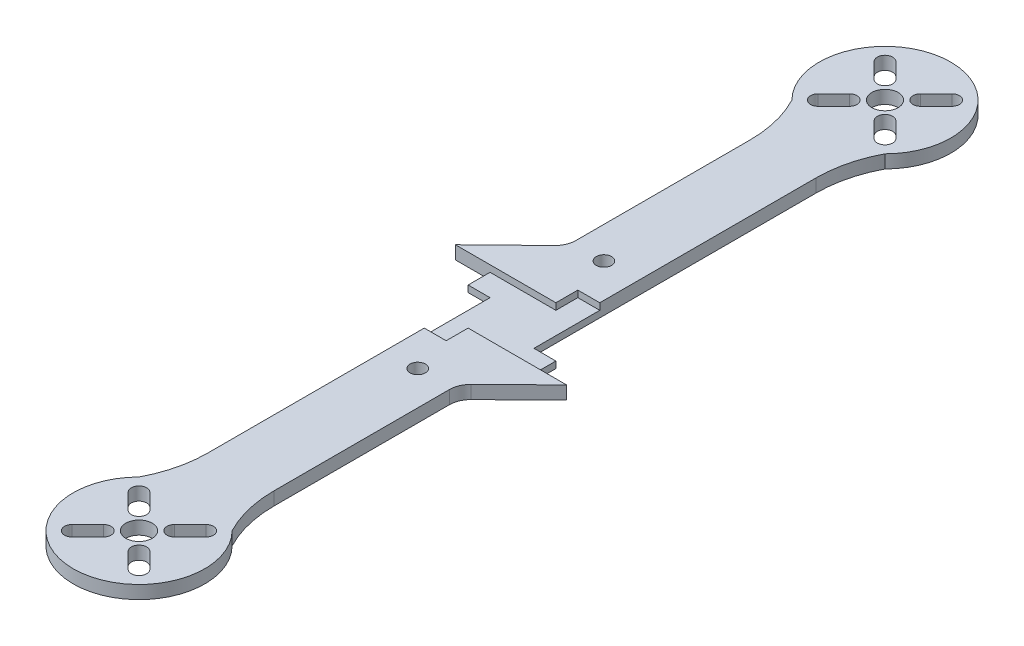
SolidWorks part; units mm, degrees
material "ABS"
ref_plane "Front Plane" through (0, 0, 0) normal (0, 0, 1) x (1, 0, 0)
ref_plane "Top Plane" through (0, 0, 0) normal (0, 1, 0) x (1, 0, 0)
ref_plane "Right Plane" through (0, 0, 0) normal (1, 0, 0) x (0, 0, -1)
sketch "Sketch1" plane through (0, 0, 0) normal (0, 1, 0) x (1, 0, 0)
  line L0 (-19.3064, 0) -> (26.0375, 0) construction
  line L3 (-7.451, -61.7809) -> (-7.451, 61.7809)
  line L4 (7.549, -61.7809) -> (7.549, 61.7809)
  arc A6 (10.6556, 74.3934) -> (-10.5576, 74.3934) centre (0.049, 85) ccw
  arc A12 (-7.451, 61.7809) -> (-10.5576, 74.3934) centre (-34.607, 61.7809) ccw
  arc A13 (7.549, 61.7809) -> (10.6556, 74.3934) centre (34.705, 61.7809) cw
  circle A14 centre (0.049, 85) radius 3
  circle A23 centre (-6.6685, 91.7175) radius 1.75
  circle A24 centre (-5.6079, 79.3431) radius 1.75
  circle A25 centre (5.7059, 90.6569) radius 1.75
  circle A26 centre (6.7665, 78.2825) radius 1.75
  circle A27 centre (0, 20) radius 1.5
  circle A28 centre (5.7059, -90.6569) radius 1.75
  circle A29 centre (-6.6685, -91.7175) radius 1.75
  circle A30 centre (0.049, -85) radius 3
  circle A31 centre (6.7665, -78.2825) radius 1.75
  circle A32 centre (-5.6079, -79.3431) radius 1.75
  arc A33 (7.549, -61.7809) -> (10.6556, -74.3934) centre (34.705, -61.7809) ccw
  arc A34 (10.6556, -74.3934) -> (-10.5576, -74.3934) centre (0.049, -85) cw
  arc A35 (-7.451, -61.7809) -> (-10.5576, -74.3934) centre (-34.607, -61.7809) cw
  circle A36 centre (0, -20) radius 1.5
  point P41 (7.549, 0)
  point P42 (-7.451, 0)
  dimension "D1" = 8
  dimension "D2" = 8
  dimension "D3" = 9.5
  dimension "D4" = 9.5
  dimension "D5" = 3.5
  dimension "D6" = 3.5
  dimension "D7" = 6
  dimension "D10" = 3.5
  dimension "D11" = 3.5
  dimension "D9" = 3
  dimension "D8" = 15
  dimension "D12" = 20
  dimension "D13" = 20
  dimension "D14" = 170
extrude "Boss-Extrude2" add sketch "Sketch1" along normal blind 3
sketch "Sketch3" plane through (0, 3, 0) normal (0, 1, 0) x (1, 0, 0)
  line L0 (-47.0006, 0) -> (46.456, 0) construction
  line L1 (7.549, -61.7809) -> (7.549, 61.7809) construction
  line L2 (-7.549, -7.5) -> (7.549, -7.5)
  line L3 (-7.549, -7.5) -> (-7.549, 7.5)
  line L4 (-7.549, 7.5) -> (7.549, 7.5)
  line L5 (7.549, -7.5) -> (7.549, 7.5)
  line L6 (-7.549, -7.5) -> (7.549, 7.5) construction
  line L7 (-7.549, 7.5) -> (7.549, -7.5) construction
  point P3 (0, 0)
  dimension "D1" = 15
extrude "Cut-Extrude1" cut sketch "Sketch3" against normal blind 1.5
sketch "Sketch4" plane through (0, 1.5, 0) normal (0, 1, 0) x (1, 0, 0)
  line L10 (-13.8473, 13.8237) -> (-7.4707, 7.5) construction
  line L11 (7.549, -7.5) -> (19.9805, -7.5)
  line L12 (7.549, -7.5) -> (7.549, -19.7239)
  line L13 (-7.2086, 7.5) -> (-20.3535, 7.5)
  line L14 (7.549, 7.5) -> (-7.451, 7.5) construction
  line L15 (-20.3535, 7.5) -> (-7.2086, 20.2761)
  line L16 (-7.2086, 20.2761) -> (-7.2086, 7.5)
  line L17 (19.9805, -7.5) -> (7.549, -19.7239)
  line L18 (7.6545, -7.5) -> (13.7913, -13.5859) construction
  point P1 (-0.1865, 0.2761)
  point P3 (0, 0)
extrude "Boss-Extrude5" add sketch "Sketch4" along normal mid plane 3
sketch "Sketch5" plane through (0, 3, 0) normal (0, 1, 0) x (1, 0, 0)
  line L18 (-2.451, -7.5) -> (-7.451, -7.5)
  line L21 (2.549, 7.5) -> (7.549, 7.5)
  line L23 (7.549, 7.5) -> (2.549, 7.5)
  line L24 (7.549, 7.5) -> (7.549, 12.5)
  line L25 (7.549, 12.5) -> (2.549, 12.5)
  line L26 (2.549, 7.5) -> (2.549, 12.5)
  line L27 (-7.451, -7.5) -> (-2.451, -7.5)
  line L28 (-7.451, -7.5) -> (-7.451, -12.5)
  line L29 (-7.451, -12.5) -> (-2.451, -12.5)
  line L30 (-2.451, -7.5) -> (-2.451, -12.5)
  line M10 (-20.3535, 7.5) -> (7.549, 7.5)
  line M11 (7.549, 7.5) -> (7.549, 61.7809)
  dimension "D1" = 5
  dimension "D2" = 5
  dimension "D3" = 5
  dimension "D4" = 5
extrude "Cut-Extrude2" cut sketch "Sketch5" against normal blind 1.5 contours L26 L25 M10 M11 | L30 L18 L28 L29
sketch "Sketch6" plane through (0, 3, 0) normal (0, 1, 0) x (1, 0, 0)
  line L0 (7.549, -19.7239) -> (8.9751, -18.3217)
  line L1 (7.549, -19.7239) -> (19.9805, -7.5) construction
  line L3 (7.549, -61.7809) -> (7.549, -19.7239) construction
  line L4 (7.549, -21.7239) -> (7.549, -19.7239)
  line L5 (-7.451, 20.0405) -> (-8.8852, 18.6465)
  line L6 (-7.451, 20.0405) -> (-20.3535, 7.5) construction
  line L8 (-7.451, 61.7809) -> (-7.451, 20.0405) construction
  line L9 (-7.451, 22.0405) -> (-7.451, 20.0405)
  arc A0 (8.9751, -18.3217) -> (7.549, -21.7239) centre (12.3205, -21.7239) ccw
  arc A1 (-8.8852, 18.6465) -> (-7.451, 22.0405) centre (-12.1839, 22.0405) ccw
  dimension "D1" = 2
  dimension "D2" = 2
  dimension "D3" = 2
  dimension "D4" = 2
extrude "Boss-Extrude7" add sketch "Sketch6" against normal blind 3
sketch "Sketch7" plane through (0, 1.5, 0) normal (0, 1, 0) x (1, 0, 0)
  line L0 (-7.451, -12.5) -> (-7.451, 7.5) construction
  line L1 (2.549, 7.5) -> (7.549, 7.5)
  line L2 (2.549, 7.5) -> (2.549, 12.5)
  line L3 (2.549, 12.5) -> (7.549, 12.5)
  line L4 (7.549, 7.5) -> (7.549, 12.5)
  line L5 (-2.451, -12.5) -> (-7.451, -12.5)
  line L6 (-2.451, -12.5) -> (-2.451, -7.5)
  line L7 (-2.451, -7.5) -> (-7.451, -7.5)
  line L8 (-7.451, -12.5) -> (-7.451, -7.5)
sketch "Sketch11" plane through (0, 1.5, 0) normal (0, 1, 0) x (1, 0, 0)
  line L1 (7.549, -7.5) -> (12.549, -7.5)
  line L2 (7.549, -7.5) -> (7.549, -2.5)
  line L3 (7.549, -2.5) -> (12.549, -2.5)
  line L4 (12.549, -7.5) -> (12.549, -2.5)
  line L5 (-7.451, 7.5) -> (-12.451, 7.5)
  line L6 (-7.451, 7.5) -> (-7.451, 2.5)
  line L7 (-7.451, 2.5) -> (-12.451, 2.5)
  line L8 (-12.451, 7.5) -> (-12.451, 2.5)
  dimension "D1" = 5
  dimension "D2" = 5
  dimension "D3" = 5
  dimension "D4" = 5
extrude "Boss-Extrude11" add sketch "Sketch11" against normal blind 1.5
sketch "Sketch13" plane through (0, 3, 0) normal (0, 1, 0) x (1, 0, 0)
  line L0 (40.0441, 0) -> (-47.62, 0) construction
  circle A0 centre (0, -20) radius 1.5
  circle A1 centre (0, 20) radius 1.5
extrude "Boss-Extrude13" add sketch "Sketch13" against normal blind 3
sketch "Sketch14" plane through (0, 3, 0) normal (0, 1, 0) x (1, 0, 0)
  line L0 (27.9035, 0) -> (-28.3453, 0) construction
  circle A0 centre (-0.2209, -21.2132) radius 1.5
  circle A1 centre (-0.2209, 21.2132) radius 1.5
  dimension "D3" = 3
  dimension "D4" = 3
  dimension "D1" = 42.4264
extrude "Cut-Extrude6" cut sketch "Sketch14" against normal through all
sketch "Sketch15" plane through (0, 3, 0) normal (0, 1, 0) x (1, 0, 0)
  circle A0 centre (-5.6079, 79.3431) radius 1.75
  circle A1 centre (6.7665, 78.2825) radius 1.75
  circle A2 centre (-6.6685, 91.7175) radius 1.75
  circle A3 centre (5.7059, 90.6569) radius 1.75
extrude "Boss-Extrude14" add sketch "Sketch15" against normal through all
sketch "Sketch16" plane through (0, 3, 0) normal (0, 1, 0) x (1, 0, 0)
  circle A2 centre (-6.6685, 78.2825) radius 1.75
  circle A3 centre (5.7059, 79.3431) radius 1.75
  circle A4 centre (6.7665, 91.7175) radius 1.75
  circle A5 centre (-5.6101, 90.6591) radius 1.75
  dimension "D5" = 3.5
  dimension "D6" = 3.5
  dimension "D7" = 3.5
  dimension "D8" = 3.5
extrude "Cut-Extrude7" cut sketch "Sketch16" against normal through all
sketch "Sketch17" plane through (0, 3, 0) normal (0, 1, 0) x (1, 0, 0)
  circle A0 centre (5.7059, 79.3431) radius 2.2546
  circle A1 centre (-6.6685, 78.2825) radius 2.9663
  circle A2 centre (-5.6101, 90.6591) radius 2.6365
  circle A3 centre (6.7665, 91.7175) radius 1.9965
  circle A4 centre (-6.6685, -91.7175) radius 2.525
  circle A5 centre (-5.6079, -79.3431) radius 3.3131
  circle A6 centre (6.7665, -78.2825) radius 2.2622
  circle A7 centre (5.7059, -90.6569) radius 2.3533
extrude "Boss-Extrude15" add sketch "Sketch17" against normal blind 3
sketch "Sketch18" plane through (0, 3, 0) normal (0, 1, 0) x (1, 0, 0)
  line L5 (0.049, -85) -> (-20.908, -85)
  line L6 (-20.908, -85) -> (24.5464, -85)
  line L11 (0.049, -105.9248) -> (0.049, -64.2488)
  line L12 (0.049, -85) -> (-2.7794, -87.8284)
  line L18 (-10.5576, -95.6066) -> (-8.7954, -93.8445)
  line L21 (0.049, -85) -> (-10.5576, -74.3934)
  line L22 (-10.5576, -74.3934) -> (0.049, -85)
  line L23 (0.049, -85) -> (10.6556, -95.6066)
  line L24 (52.5615, 0) -> (-59.544, 0) construction
  line L25 (0.049, -85) -> (-2.7794, -87.8284)
  line L30 (6.0476, -79.0014) -> (-2.7794, -87.8284) construction
  line L31 (8.8935, -91.3696) -> (5.3523, -87.8284)
  line L33 (0.049, -85) -> (-2.7794, -87.8284)
  line L34 (6.4186, -93.8445) -> (2.8774, -90.3033)
  line L35 (-6.3206, -93.8445) -> (-2.7794, -90.3033)
  line L37 (-8.7954, -91.3696) -> (-5.2543, -87.8284)
  line L40 (-2.7794, -87.8284) -> (10.6556, -74.3934)
  line L41 (8.8935, -78.6304) -> (5.3523, -82.1716)
  line L42 (6.4186, -76.1555) -> (2.8774, -79.6967)
  line L43 (-6.3206, -76.1555) -> (-2.7794, -79.6967)
  line L45 (-8.7954, -93.8445) -> (-10.5576, -95.6066)
  line L46 (-8.7954, -78.6304) -> (-5.2543, -82.1716)
  line L47 (-8.7954, 78.6304) -> (-5.2543, 82.1716)
  line L48 (-6.3206, 76.1555) -> (-2.7794, 79.6967)
  line L49 (6.4186, 76.1555) -> (2.8774, 79.6967)
  line L50 (8.8935, 78.6304) -> (5.3523, 82.1716)
  line L51 (-8.7954, 91.3696) -> (-5.2543, 87.8284)
  line L52 (-6.3206, 93.8445) -> (-2.7794, 90.3033)
  line L53 (8.8935, 91.3696) -> (5.3523, 87.8284)
  line L54 (6.4186, 93.8445) -> (2.8774, 90.3033)
  arc A12 (-2.7794, -90.3033) -> (-5.2543, -87.8284) centre (-4.0169, -89.0659) ccw
  arc A14 (-8.7954, -91.3696) -> (-6.3206, -93.8445) centre (-7.558, -92.607) ccw
  arc A17 (8.8935, -91.3696) -> (6.4186, -93.8445) centre (7.656, -92.607) cw
  circle A18 centre (0.049, -85) radius 15
  arc A19 (2.8774, -90.3033) -> (5.3523, -87.8284) centre (4.1149, -89.0659) cw
  arc A20 (2.8774, -79.6967) -> (5.3523, -82.1716) centre (4.1149, -80.9341) ccw
  arc A21 (8.8935, -78.6304) -> (6.4186, -76.1555) centre (7.656, -77.393) ccw
  arc A22 (-8.7954, -78.6304) -> (-6.3206, -76.1555) centre (-7.558, -77.393) cw
  arc A23 (-2.7794, -79.6967) -> (-5.2543, -82.1716) centre (-4.0169, -80.9341) cw
  arc A24 (-2.7794, 79.6967) -> (-5.2543, 82.1716) centre (-4.0169, 80.9341) ccw
  arc A25 (-8.7954, 78.6304) -> (-6.3206, 76.1555) centre (-7.558, 77.393) ccw
  arc A26 (8.8935, 78.6304) -> (6.4186, 76.1555) centre (7.656, 77.393) cw
  arc A27 (2.8774, 79.6967) -> (5.3523, 82.1716) centre (4.1149, 80.9341) cw
  arc A28 (-8.7954, 91.3696) -> (-6.3206, 93.8445) centre (-7.558, 92.607) cw
  arc A29 (-2.7794, 90.3033) -> (-5.2543, 87.8284) centre (-4.0169, 89.0659) cw
  arc A30 (2.8774, 90.3033) -> (5.3523, 87.8284) centre (4.1149, 89.0659) ccw
  arc A31 (8.8935, 91.3696) -> (6.4186, 93.8445) centre (7.656, 92.607) ccw
  dimension "D1" = 4
  dimension "D2" = 3.5
  dimension "D3" = 3.5
sketch "Sketch19" plane through (0, 3, 0) normal (0, 1, 0) x (1, 0, 0)
  circle A0 centre (-0.2209, -21.2132) radius 1.75
  circle A1 centre (-0.2209, 21.2132) radius 1.75
  dimension "D1" = 3.5
  dimension "D2" = 3.5
extrude "Cut-Extrude10" cut sketch "Sketch19" against normal blind 10 contours A1 | A0
extrude "Cut-Extrude11" cut sketch "Sketch18" against normal blind 10 contours A19 L34 A17 L23 | A19 L23 A17 L31 | L41 A21 L40 A20 | L40 A21 L42 A20 | L37 A14 L35 A12 | A23 L22 A22 L46 | A23 L43 A22 L22 | A29 L52 A28 L51 | L53 A31 L54 A30 | A27 L49 A26 L50 | L47 A25 L48 A24
